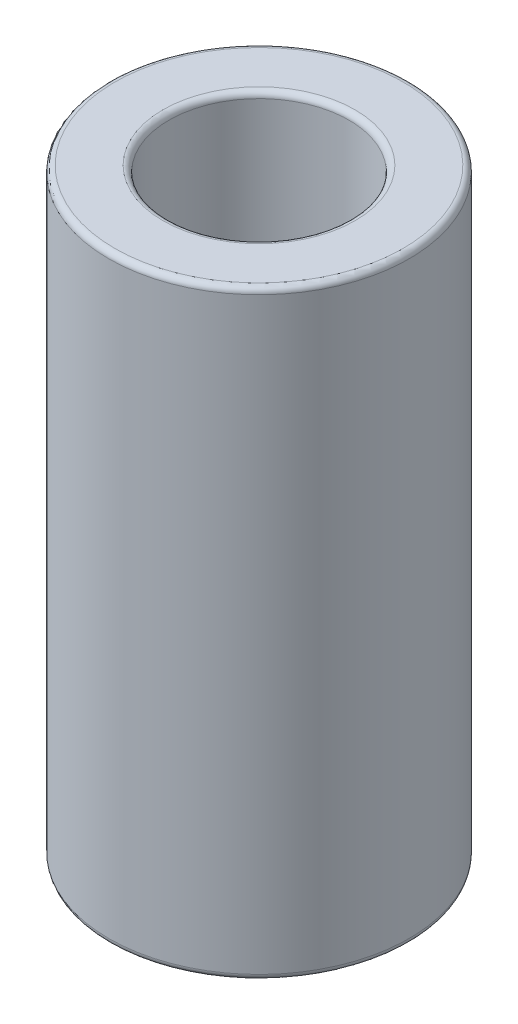
SolidWorks part; units mm, degrees
material "2.0966 (CuAl10Ni5Fe4)"
ref_plane "前视基准面" through (0, 0, 0) normal (0, 0, 1) x (1, 0, 0)
ref_plane "上视基准面" through (0, 0, 0) normal (0, 1, 0) x (1, 0, 0)
ref_plane "右视基准面" through (0, 0, 0) normal (1, 0, 0) x (0, 0, -1)
sketch "草图1" plane through (0, 0, 0) normal (0, 1, 0) x (1, 0, 0)
  circle A0 centre (0, 0) radius 1.5
  circle A1 centre (0, 0) radius 2.5
  dimension "D1" = 3
  dimension "D2" = 5
extrude "凸台-拉伸1" add sketch "草图1" along normal blind 10
fillet "圆角1" radius 0.1 4 edges at (0, 0, 1.5) (0, 10, 1.5) (0, 0, 2.5) (0, 10, 2.5)
